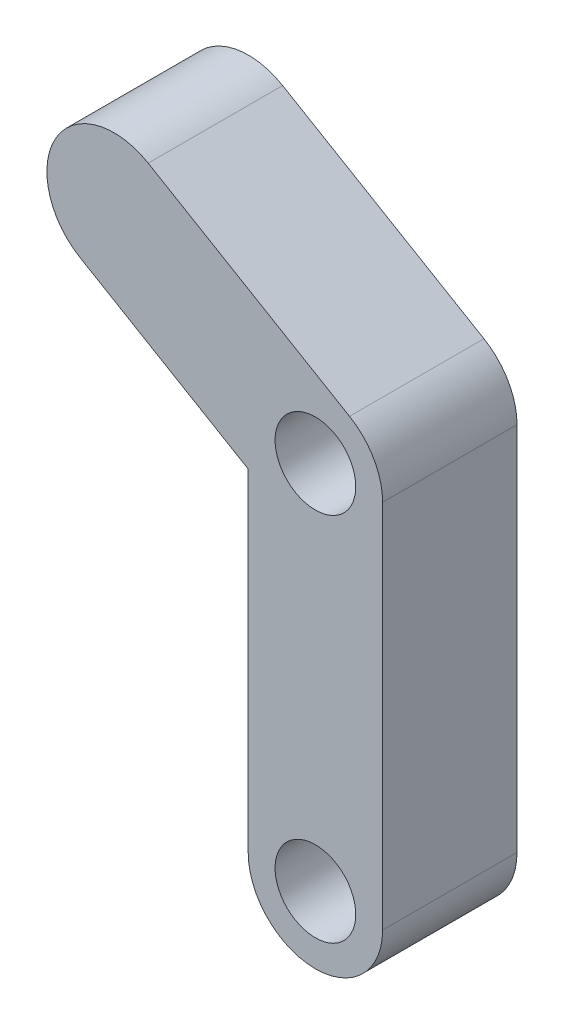
SolidWorks part; units mm, degrees
ref_plane "Ebene vorne" through (0, 0, 0) normal (0, 0, 1) x (1, 0, 0)
ref_plane "Ebene oben" through (0, 0, 0) normal (0, 1, 0) x (1, 0, 0)
ref_plane "Ebene rechts" through (0, 0, 0) normal (1, 0, 0) x (0, 0, -1)
sketch "Skizze1" plane through (0, 0, 0) normal (0, 0, 1) x (1, 0, 0)
  line L0 (0, 0) -> (0, 13.78) construction
  line L1 (-2.5, 13.78) -> (-2.5, 0)
  line L2 (2.5, 13.78) -> (2.5, 0)
  line L4 (-6.2192, 20.3449) -> (1.2688, 15.9341)
  line L5 (-2.5, 12.3511) -> (-8.7569, 16.0367)
  circle A0 centre (0, 0) radius 1.5
  circle A1 centre (0, 0) radius 2.5
  circle A2 centre (0, 13.78) radius 1.5
  circle A3 centre (0, 13.78) radius 2.5
  circle A4 centre (-7.4881, 18.1908) radius 2.5
  dimension "D1" = 5
  dimension "D2" = 3
  dimension "D3" = 3
  dimension "D4" = 5
  dimension "D5" = 13.78
  dimension "D6" = 5
  dimension "D7" = 120.5
extrude "Aufsatz-Linear austragen1" add sketch "Skizze1" along normal blind 5
